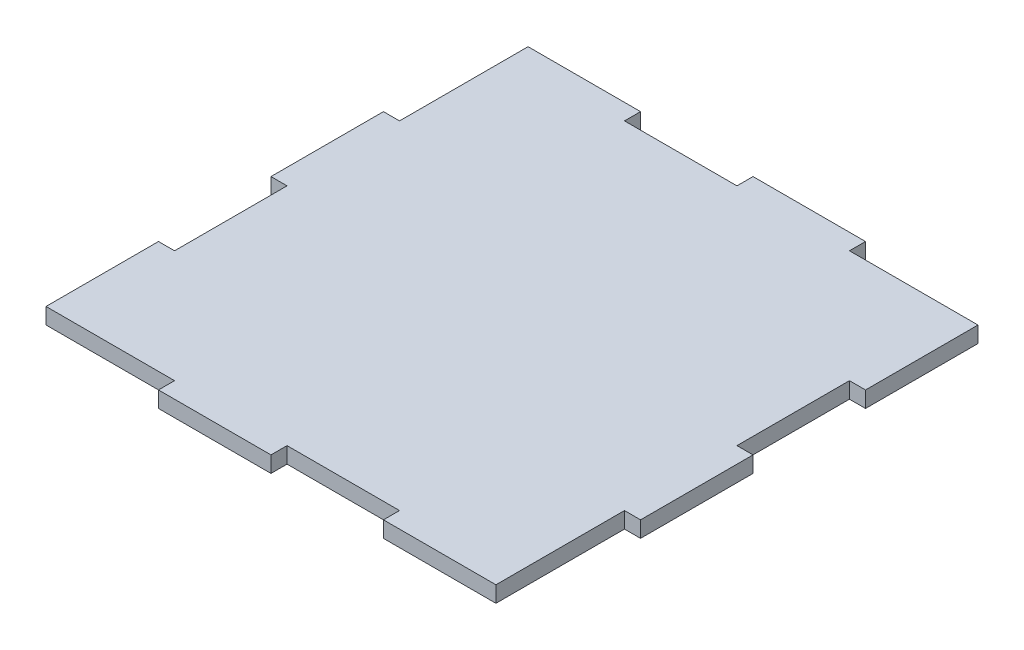
SolidWorks part; units mm, degrees
material "Acrylic (Medium-high impact)"
ref_plane "Front Plane" through (0, 0, 0) normal (0, 0, 1) x (1, 0, 0)
ref_plane "Top Plane" through (0, 0, 0) normal (0, 1, 0) x (1, 0, 0)
ref_plane "Right Plane" through (0, 0, 0) normal (1, 0, 0) x (0, 0, -1)
sketch "Sketch1" plane through (0, 0, 0) normal (0, 1, 0) x (1, 0, 0)
  line L0 (-112.5062, -84.4873) -> (-118.8562, -84.4873)
  line L1 (-112.5062, 93.3127) -> (65.2938, 93.3127)
  line L2 (-112.5062, 93.3127) -> (-112.5062, -84.4873)
  line L3 (-112.5062, -84.4873) -> (65.2938, -84.4873)
  line L4 (65.2938, 93.3127) -> (65.2938, -84.4873)
  line L5 (-118.8562, -84.4873) -> (-118.8562, -40.0373)
  line L6 (-118.8562, -40.0373) -> (-112.5062, -40.0373)
  line L7 (-112.5062, -84.4873) -> (-118.8562, -84.4873)
  line L8 (-112.5062, -40.0373) -> (-112.5062, 4.4127)
  line L9 (-112.5062, 4.4127) -> (-118.8562, 4.4127)
  line L10 (-118.8562, 4.4127) -> (-118.8562, 48.8627)
  line L11 (-118.8562, 48.8627) -> (-112.5062, 48.8627)
  line L12 (-112.5062, 93.3127) -> (-112.5062, 99.6627)
  line L13 (-112.5062, 99.6627) -> (-68.0562, 99.6627)
  line L14 (-68.0562, 99.6627) -> (-68.0562, 93.3127)
  line L15 (-23.6062, 93.3127) -> (-23.6062, 99.6627)
  line L16 (-23.6062, 99.6627) -> (20.8438, 99.6627)
  line L17 (20.8438, 99.6627) -> (20.8438, 93.3127)
  line L18 (65.2938, 93.3127) -> (71.6438, 93.3127)
  line L19 (71.6438, 93.3127) -> (71.6438, 48.8627)
  line L20 (71.6438, 48.8627) -> (65.2938, 48.8627)
  line L21 (65.2938, 4.4127) -> (71.6438, 4.4127)
  line L22 (71.6438, 4.4127) -> (71.6438, -40.0373)
  line L23 (71.6438, -40.0373) -> (65.2938, -40.0373)
  line L24 (65.2938, -84.4873) -> (65.2938, -90.8373)
  line L25 (65.2938, -90.8373) -> (20.8438, -90.8373)
  line L26 (20.8438, -90.8373) -> (20.8438, -84.4873)
  line L27 (-23.6062, -84.4873) -> (-23.6062, -90.8373)
  line L28 (-23.6062, -90.8373) -> (-68.0562, -90.8373)
  line L29 (-68.0562, -90.8373) -> (-68.0562, -84.4873)
  point P4 (-23.6062, 93.3127)
  point P5 (-112.5062, 4.4127)
  point P6 (-112.5062, -40.0373)
  point P7 (-112.5062, 4.4127)
  point P9 (65.2938, 4.4127)
  point P10 (-23.6062, -84.4873)
  point P11 (-23.6062, 4.4127)
  point P14 (-112.5062, 48.8627)
  point P47 (-23.6062, 4.4127)
  dimension "D1" = 177.8
  dimension "D2" = 177.8
  dimension "D3" = 44.45
  dimension "D4" = 44.45
  dimension "D5" = 44.45
  dimension "D6" = 6.35
  dimension "D7" = 6.35
  dimension "D8" = 4
extrude "Boss-Extrude1" add sketch "Sketch1" along normal blind 6.35
